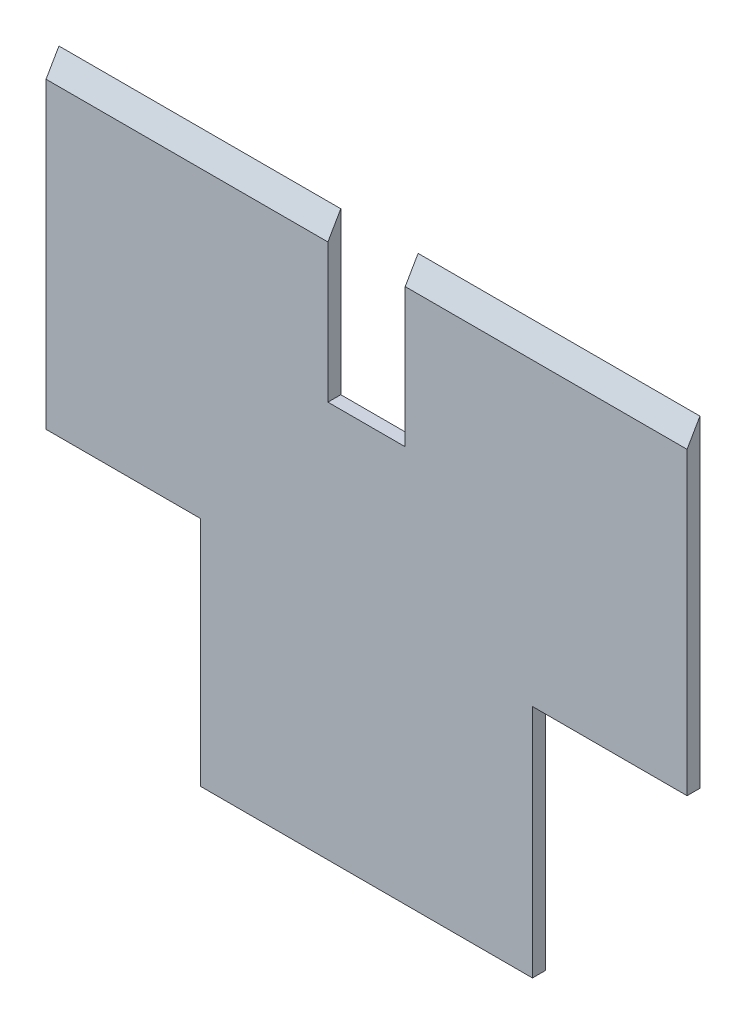
SolidWorks part; units mm, degrees
ref_plane "Alzado" through (0, 0, 0) normal (0, 0, 1) x (1, 0, 0)
ref_plane "Planta" through (0, 0, 0) normal (0, 1, 0) x (1, 0, 0)
ref_plane "Vista lateral" through (0, 0, 0) normal (1, 0, 0) x (0, 0, -1)
sketch "Croquis1" plane through (0, 0, 0) normal (0, 0, 1) x (1, 0, 0)
  line L4 (100, 100) -> (100, 42)
  line L10 (76, 0) -> (24, 0)
  line L11 (24, 42) -> (0, 42)
  line L14 (24, 42) -> (24, 0)
  line L16 (76, 42) -> (76, 0)
  line L17 (0, 42) -> (0, 100)
  line L18 (0, 100) -> (100, 100)
  line L19 (100, 42) -> (76, 42)
extrude "Saliente-Extruir1" add sketch "Croquis1" along normal blind 2
sketch "Croquis4" plane through (0, 0, 0) normal (-1, 0, 0) x (0, 0, 1)
  line L1 (2, 89.0656) -> (2, 91.0656)
  line L2 (2, 93.0667) -> (2, 91.0656)
  line L3 (0, 100) -> (0, 42) construction
  line L4 (2, 91.0656) -> (2, 93.0667) construction
  line L5 (2, 93.0667) -> (2, 100)
  line L7 (2, 42) -> (0, 42) construction
  line L11 (0, 96.5333) -> (0, 94.5322)
  line L13 (2, 100) -> (0, 100)
  line L14 (0, 100) -> (0, 96.5333)
  line L15 (0, 94.5322) -> (0, 92.5322) construction
  line L17 (0, 92.5322) -> (2, 89.0656)
  line L19 (0, 92.5322) -> (0, 94.5322)
  dimension "D1" = 47.0656
  dimension "D2" = 50.5322
  dimension "D3" = 51.0667
extrude "Cortar-Extruir2" cut sketch "Croquis4" against normal up to vertex
sketch "Croquis5" plane through (0, 0, 0) normal (0, 0, -1) x (-1, 0, 0)
  line L0 (-76, 13.3326) -> (-70.1456, 13.3326) construction
  line L1 (-76, 0) -> (-76, 42) construction
sketch "Croquis6" plane through (0, 0, 0) normal (0, 0, -1) x (-1, 0, 0)
  line L0 (-100, 92.5322) -> (-99.5, 92.5322)
  line L1 (-100, 92.5322) -> (0, 92.5322) construction
  line L2 (-99.5, 92.5322) -> (-99.5, 42.5)
  line L4 (-75.5028, 0) -> (-75.5028, 42.5)
  line L5 (-100, 42) -> (-100, 92.5322)
  line L6 (-76, 0) -> (-75.5028, 0)
  line L7 (-24, 0) -> (-76, 0) construction
  line L8 (-76, 0) -> (-76, 42)
  line L9 (-76, 42) -> (-100, 42)
  line L10 (-100, 42) -> (-100, 92.5322) construction
  line L11 (-75.5028, 42.5) -> (-99.5, 42.5)
  dimension "D1" = 0.5
  dimension "D2" = 24.4972
  dimension "D3" = 50.0322
extrude "Cortar-Extruir3" cut sketch "Croquis6" against normal up to vertex (2 mm away)
sketch "Croquis7" plane through (0, 0, 0) normal (0, 0, -1) x (-1, 0, 0)
  line L0 (-49.75, 92.5322) -> (-49.75, 67.5322) construction
  line L1 (-99.5, 92.5322) -> (0, 92.5322) construction
  line L2 (-49.75, 67.5322) -> (-43.75, 67.5322) construction
  line L3 (-49.75, 67.5322) -> (-55.75, 67.5322) construction
  line L4 (-99.5, 42.5) -> (-99.5, 92.5322) construction
  line L5 (-55.75, 67.5322) -> (-43.75, 67.5322)
  line L6 (-55.75, 67.5322) -> (-55.75, 92.5322)
  line L7 (-55.75, 92.5322) -> (-43.75, 92.5322)
  line L8 (-43.75, 67.5322) -> (-43.75, 92.5322)
  line L9 (-24, 0) -> (-75.5028, 0) construction
  dimension "D1" = 43.75
  dimension "D2" = 67.5322
extrude "Cortar-Extruir4" cut sketch "Croquis7" against normal up to vertex (2 mm away)
sketch "Croquis9" plane through (75.5028, 0, 0) normal (1, 0, 0) x (0, 0, -1)
  line L0 (0, 0) -> (0, 6)
  line L1 (0, 0) -> (0, 42.5) construction
  line L2 (0, 6) -> (-2, 6)
  line L3 (-2, 0) -> (-2, 42.5) construction
  line L4 (-2, 6) -> (-2, 0)
  line L5 (-2, 0) -> (0, 0)
  line L6 (-2, 42.5) -> (0, 42.5) construction
  dimension "D1" = 36.5
extrude "Cortar-Extruir5" cut sketch "Croquis9" against normal up to vertex
